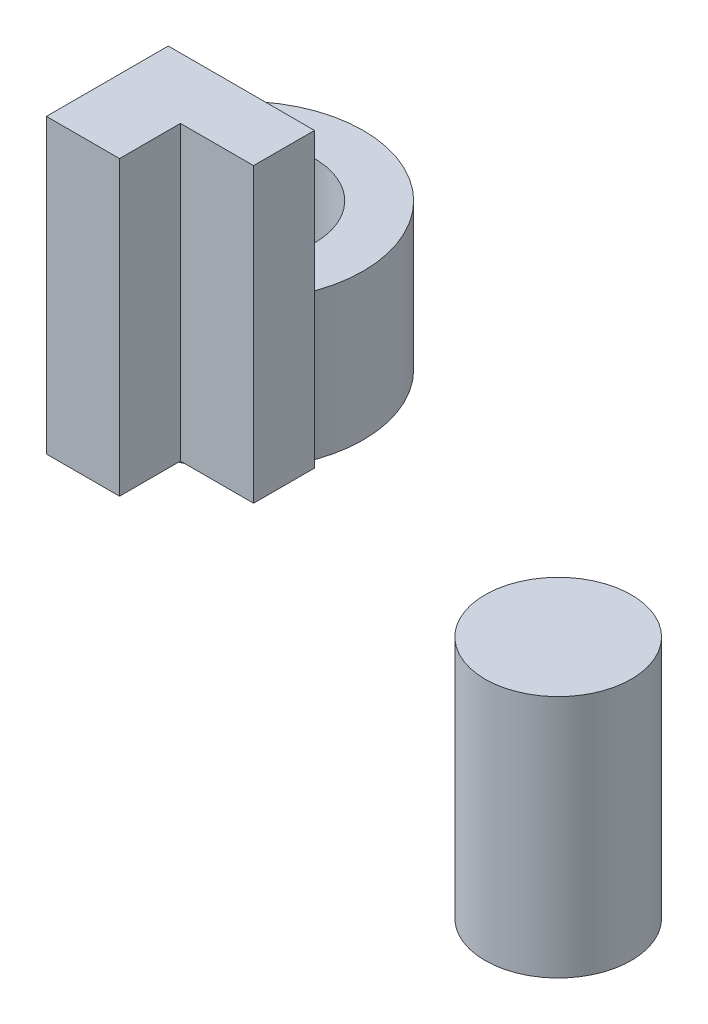
SolidWorks part; units mm, degrees
ref_plane "Přední rovina" through (0, 0, 0) normal (0, 0, 1) x (1, 0, 0)
ref_plane "Horní rovina" through (0, 0, 0) normal (0, 1, 0) x (1, 0, 0)
ref_plane "Pravá rovina" through (0, 0, 0) normal (1, 0, 0) x (0, 0, -1)
sketch "Skica1" plane through (0, 0, 0) normal (0, 1, 0) x (1, 0, 0)
  line L0 (20, -35) -> (50, -35)
  line L1 (20, -35) -> (20, -60)
  line L2 (50, -35) -> (50, -60)
  line L3 (20, -60) -> (50, -60)
  line L4 (35, -60) -> (35, -47.5)
  line L5 (35, -47.5) -> (50, -47.5)
  circle A0 centre (100, -35) radius 15
  point P7 (0, 0)
  point P8 (0, 0)
  dimension "D5" = 30
  dimension "D6" = 100
  dimension "D1" = 25
  dimension "D2" = 30
  dimension "D3" = 35
  dimension "D4" = 20
extrude "Přidat vysunutím1" add sketch "Skica1" along normal blind 60 from offset 40 contours L4 L5 L2 L0 L1 L3
sketch "Skica2" plane through (0, 0, 0) normal (0, 1, 0) x (1, 0, 0)
  line L0 (20, -35) -> (50, -35) construction
  circle A0 centre (100, -35) radius 15
  point P2 (0, 0)
  dimension "D1" = 30
  dimension "D2" = 100
extrude "Přidat vysunutím2" add sketch "Skica2" along normal blind 50 from offset 15 separate body offset against normal yes
sketch "Skica4" plane through (0, 0, 0) normal (0, 0, 1) x (1, 0, 0)
  line L0 (15, 45) -> (25, 45)
  line L1 (15, 45) -> (15, 15)
  line L2 (25, 45) -> (25, 15)
  line L3 (15, 15) -> (25, 15)
  line L4 (0, 85.8556) -> (0, -24.3504) construction
  dimension "D1" = 10
  dimension "D2" = 30
  dimension "D3" = 15
  dimension "D4" = 15
revolve "Rotovat1" add sketch "Skica4" angle 360 about L4
